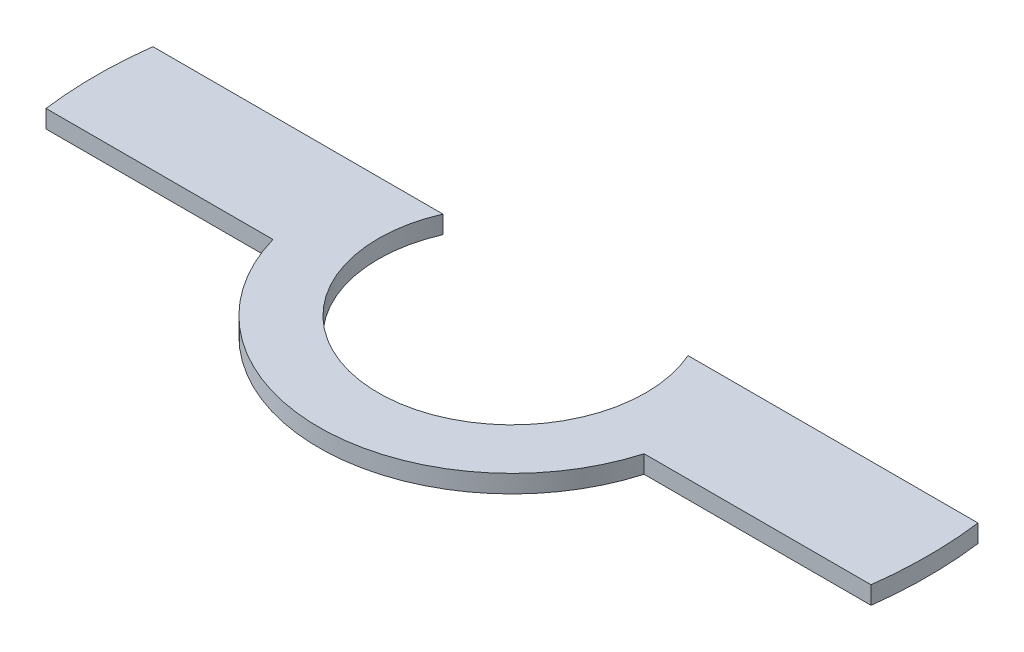
SolidWorks part; units mm, degrees
ref_plane "Alzado" through (0, 0, 0) normal (0, 0, 1) x (1, 0, 0)
ref_plane "Planta" through (0, 0, 0) normal (0, 1, 0) x (1, 0, 0)
ref_plane "Vista lateral" through (0, 0, 0) normal (1, 0, 0) x (0, 0, -1)
sketch "Croquis1" plane through (0, 0, 0) normal (0, 1, 0) x (1, 0, 0)
  line L105 (-31.229, -9) -> (-69.419, -9)
  line L106 (-20.6216, 9) -> (-69.419, 9)
  line L107 (20.6216, 9) -> (69.419, 9)
  line L108 (31.229, -9) -> (69.419, -9)
  arc A0 (69.419, -9) -> (69.419, 9) centre (0, 0) ccw
  arc A1 (-20.6216, 9) -> (20.6216, 9) centre (0, 0) ccw
  arc A2 (-69.419, 9) -> (-69.419, -9) centre (0, 0) ccw
  arc A3 (-31.229, -9) -> (31.229, -9) centre (0, 0) ccw
extrude "Saliente-Extruir1" add sketch "Croquis1" along normal blind 3
